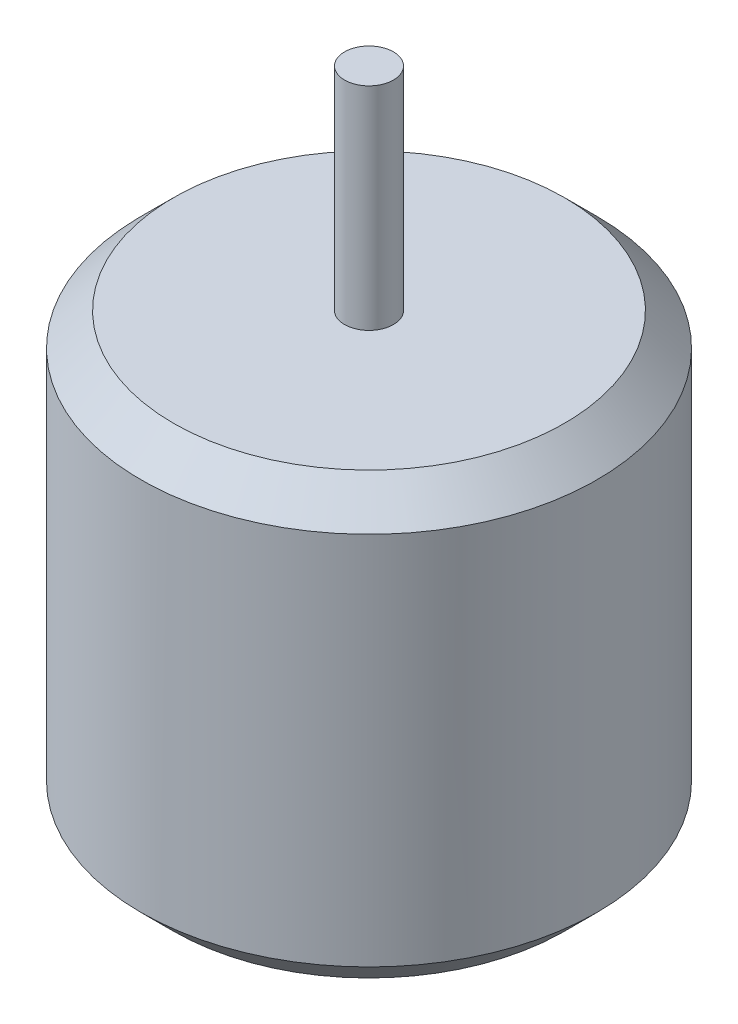
SolidWorks part; units mm, degrees
ref_plane "Front Plane" through (0, 0, 0) normal (0, 0, 1) x (1, 0, 0)
ref_plane "Top Plane" through (0, 0, 0) normal (0, 1, 0) x (1, 0, 0)
ref_plane "Right Plane" through (0, 0, 0) normal (1, 0, 0) x (0, 0, -1)
sketch "Sketch1" plane through (0, 0, 0) normal (0, 1, 0) x (1, 0, 0)
  line L0 (0, 0) -> (0, 23.033) construction
  line L1 (0, 0) -> (-19.4801, 19.4801) construction
  line L2 (0, 0) -> (19.4801, 19.4801) construction
  circle A0 centre (0, 0) radius 14
  circle A1 centre (-6.7175, 6.7175) radius 1.6
  circle A2 centre (5.6569, 5.6569) radius 1.6
  circle A3 centre (0, 0) radius 4.25
  circle A4 centre (6.7175, -6.7175) radius 1.6
  circle A5 centre (-5.6569, -5.6569) radius 1.6
  dimension "D1" = 28
  dimension "D3" = 3.2
  dimension "D4" = 3.2
  dimension "D7" = 8.5
  dimension "D2" = 45
  dimension "D5" = 9.5
  dimension "D6" = 8
extrude "Boss-Extrude1" add sketch "Sketch1" along normal blind 26
chamfer "Chamfer1" distance 2 angle 45 1 edges at (0, 0, 14)
sketch "Sketch2" plane through (0, 26, 0) normal (0, 1, 0) x (1, 0, 0)
  circle A0 centre (0, 0) radius 14
extrude "Boss-Extrude2" add sketch "Sketch2" along normal blind 1
chamfer "Chamfer2" distance 2 angle 45 1 edges at (0, 27, 14)
sketch "Sketch4" plane through (0, 27, 0) normal (0, 1, 0) x (1, 0, 0)
  circle A0 centre (0, 0) radius 1.5
extrude "Boss-Extrude3" add sketch "Sketch4" along normal blind 13
